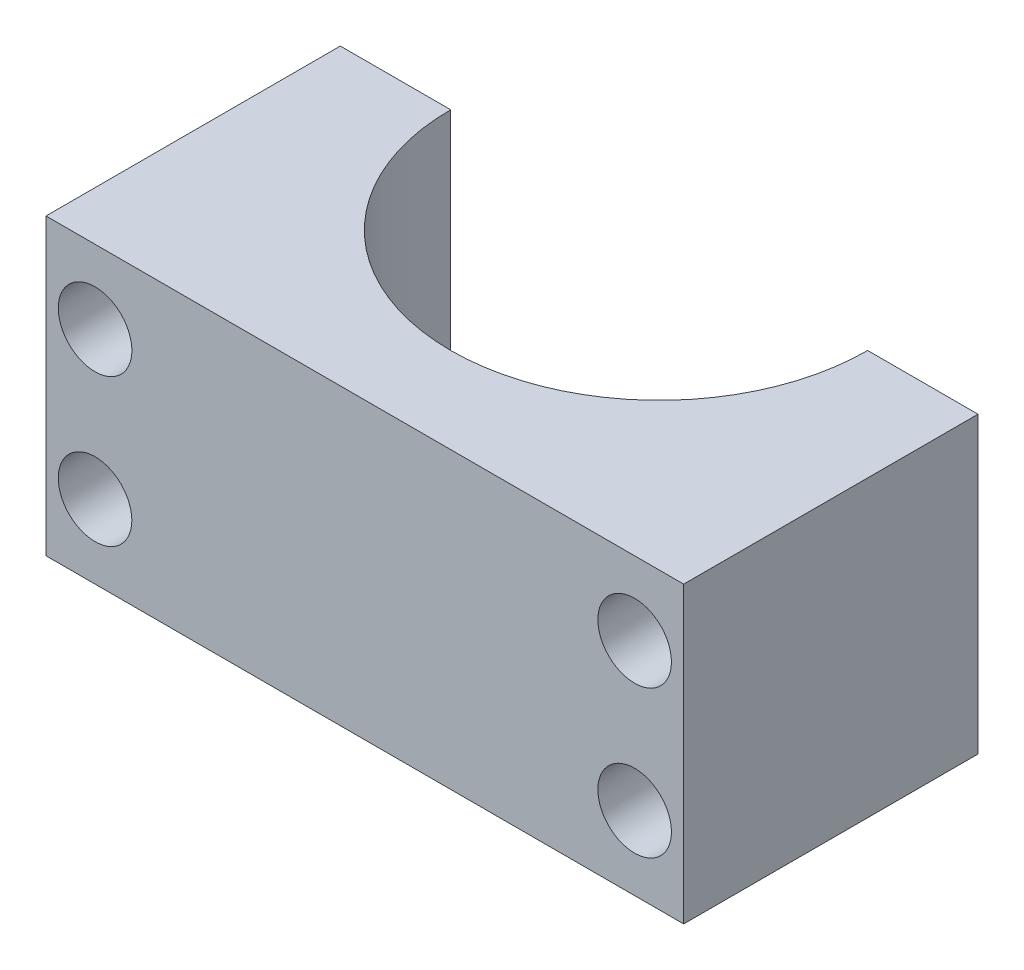
SolidWorks part; units mm, degrees
ref_plane "前视基准面" through (0, 0, 0) normal (0, 0, 1) x (1, 0, 0)
ref_plane "上视基准面" through (0, 0, 0) normal (0, 1, 0) x (1, 0, 0)
ref_plane "右视基准面" through (0, 0, 0) normal (1, 0, 0) x (0, 0, -1)
sketch "草图1" plane through (0, 0, 0) normal (0, 1, 0) x (1, 0, 0)
  line L2 (-1020.5951, 0) -> (-8.5, 0) construction
  line L3 (-13, 0) -> (-8.5, 0)
  line L5 (-13, 0) -> (-13, -12)
  line L6 (-13, -12) -> (13, -12)
  line L7 (13, 0) -> (13, -12)
  line L8 (6.4982, -5.4794) -> (13, -12) construction
  line L9 (-13, -12) -> (-6.4982, -5.4794) construction
  line L10 (8.5, 0) -> (13, 0)
  line L12 (8.5, 0) -> (50009.1597, 0) construction
  arc A0 (-8.5, 0) -> (8.5, 0) centre (0, 0) ccw
  dimension "D2" = 8.5
  dimension "D1" = 26
  dimension "D3" = 4.5
  dimension "D4" = 12
extrude "凸台-拉伸1" add sketch "草图1" along normal blind 12
sketch "草图2" plane through (0, 0, 12) normal (0, 0, 1) x (1, 0, 0)
  line L0 (0, 12) -> (0, -0.0005) construction
  line L1 (-13, 12) -> (13, 12) construction
  line L2 (-13, 12) -> (-13, 0) construction
  line L3 (-13, 0) -> (13, 0) construction
  line L4 (-1000, 5.9998) -> (49000, 5.9998) construction
  circle A0 centre (-11, 3) radius 1.5
  circle A1 centre (11, 3) radius 1.5
  circle A2 centre (11, 8.9995) radius 1.5
  circle A3 centre (-11, 8.9995) radius 1.5
  point P15 (0, 5.9998)
  dimension "D1" = 3
  dimension "D2" = 2
  dimension "D3" = 3
extrude "切除-拉伸1" cut sketch "草图2" against normal blind 12
